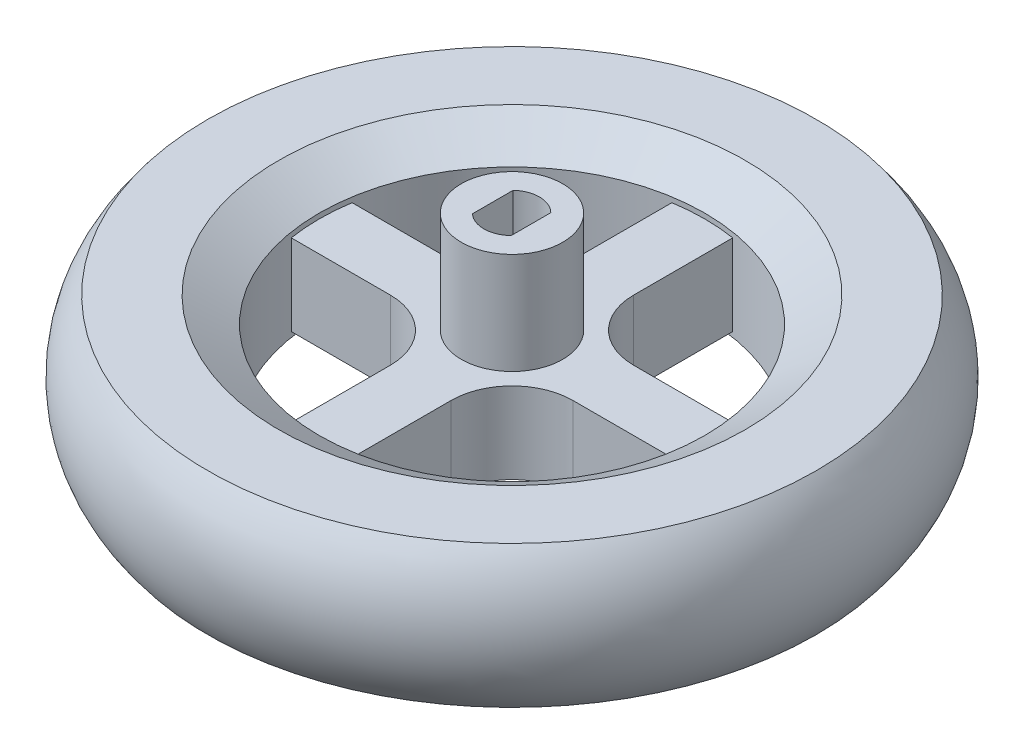
SolidWorks part; units mm, degrees
ref_plane "Front Plane" through (0, 0, 0) normal (0, 0, 1) x (1, 0, 0)
ref_plane "Top Plane" through (0, 0, 0) normal (0, 1, 0) x (1, 0, 0)
ref_plane "Right Plane" through (0, 0, 0) normal (1, 0, 0) x (0, 0, -1)
sketch "Sketch2" plane through (0, 0, 0) normal (0, 0, 1) x (1, 0, 0)
  line L0 (0, 0) -> (-32.5, 0) construction
  line L1 (0, -7) -> (0, 7) construction
  line L2 (-23, -7) -> (-23, 7) construction
  line L3 (-19, -4.5) -> (-19, 4.5)
  line L4 (-23, 7) -> (-19, 4.5)
  line L5 (-23, 7) -> (-30, 7)
  line L6 (-23, -7) -> (-30, -7)
  line L7 (-23, -7) -> (-19, -4.5)
  arc A0 (-30, -7) -> (-30, 7) centre (-21.45, 0) cw
  point P6 (0, 0)
  point P9 (-23, 0)
  point P12 (-19, 0)
  dimension "D1" = 11.05
  dimension "D8" = 32.5
  dimension "D2" = 14
  dimension "D3" = 14
  dimension "D4" = 4
  dimension "D5" = 9
  dimension "D6" = 11.05
  dimension "D7" = 7
revolve "Revolve1" add sketch "Sketch2" angle 360 about L1
ref_plane "Plane1" through (0, 0, 0) normal (0, 1, 0) x (1, 0, 0)
sketch "Sketch3" plane through (0, 0, 0) normal (0, 1, 0) x (1, 0, 0)
  line L0 (0, 0) -> (34.28, 0) construction
  line L6 (0.098, 22.9808) -> (-0.098, -22.9808) construction
  line L7 (0, -19) -> (0, 19) construction
  line L8 (9, 3) -> (25, 3)
  line L9 (-3, -25) -> (3, -25)
  line L10 (-3, -25) -> (-3, -9)
  line L11 (-3, 25) -> (3, 25)
  line L12 (3, -25) -> (3, -9)
  line L13 (-3, -25) -> (3, 25) construction
  line L14 (-3, 25) -> (3, -25) construction
  line L15 (-25, -3) -> (-9, -3)
  line L16 (-25, -3) -> (-25, 3)
  line L17 (-25, 3) -> (-9, 3)
  line L18 (25, -3) -> (25, 3)
  line L19 (-25, -3) -> (25, 3) construction
  line L20 (-25, 3) -> (25, -3) construction
  line L22 (-3, 9) -> (-3, 25)
  line L23 (3, 9) -> (3, 25)
  line L25 (9, -3) -> (25, -3)
  circle A0 centre (0, 0) radius 19 construction
  arc A1 (3, -9) -> (9, -3) centre (9, -9) cw
  arc A2 (9, 3) -> (3, 9) centre (9, 9) cw
  arc A3 (-9, 3) -> (-3, 9) centre (-9, 9) ccw
  arc A4 (-9, -3) -> (-3, -9) centre (-9, -9) cw
  point P12 (0, 0)
  point P34 (3, -3)
  point P37 (3, 3)
  point P40 (-3, 3)
  dimension "D8" = 6
  dimension "D4" = 6
  dimension "D5" = 50
  dimension "D6" = 50
  dimension "D7" = 6
extrude "Boss-Extrude1" add sketch "Sketch3" along normal blind 4 and the other way blind 4
sketch "Sketch4" plane through (0, 4, 0) normal (0, 1, 0) x (1, 0, 0)
  circle A4 centre (0, 0) radius 5
  dimension "D1" = 10
extrude "Boss-Extrude2" add sketch "Sketch4" along normal blind 10
sketch "Sketch5" plane through (0, 14, 0) normal (0, 1, 0) x (1, 0, 0)
  line L2 (-1.885, -2.0172) -> (-1.885, 2.0022)
  line L4 (1.885, -1.9603) -> (1.885, 1.9452)
  line L5 (-1.85, -6.1901) -> (1.85, 6.1901) construction
  line L6 (6.2437, 1.5679) -> (-6.3036, -1.5829) construction
  arc A0 (-1.885, -2.0172) -> (1.885, -1.9603) centre (-0.0299, -0.0075) ccw
  arc A1 (1.885, 1.9452) -> (-1.885, 2.0022) centre (-0.0299, -0.0075) ccw
  point P0 (0, 0)
  dimension "D1" = 5.47
  dimension "D2" = 1.885
  dimension "D3" = 3.77
extrude "Cut-Extrude1" cut sketch "Sketch5" against normal blind 9
